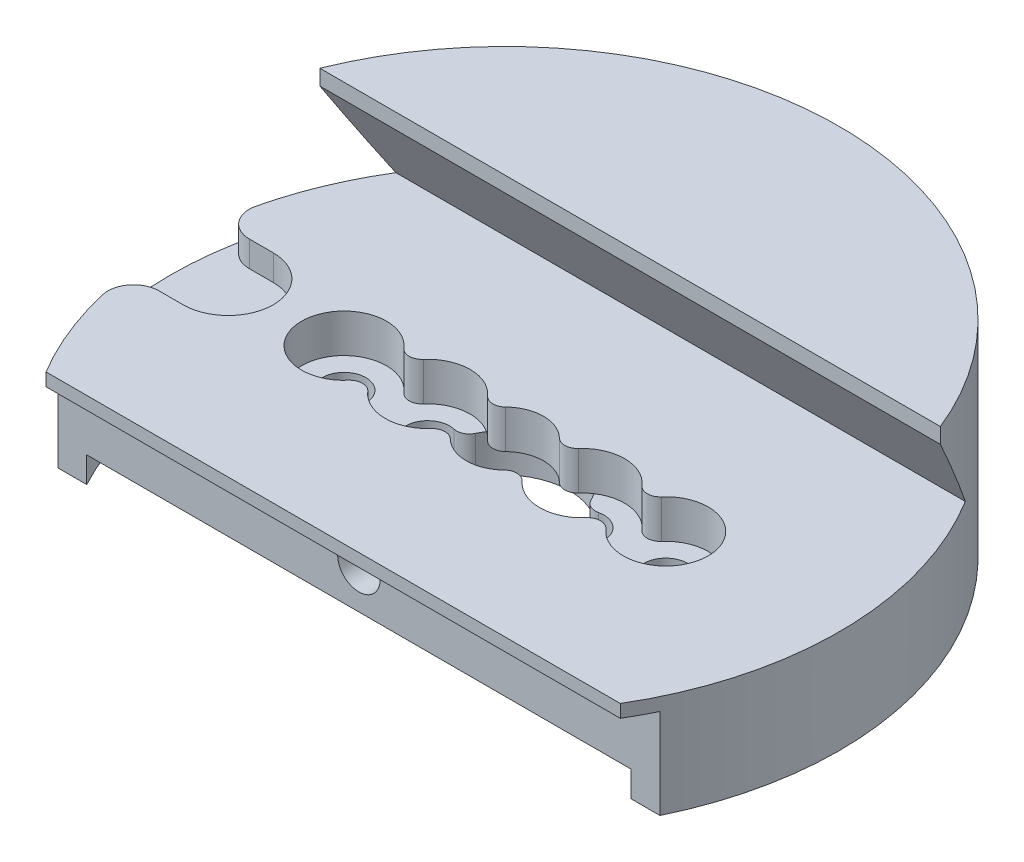
SolidWorks part; units mm, degrees
material "Сплав 2024"
ref_plane "Спереди" through (0, 0, 0) normal (0, 0, 1) x (1, 0, 0)
ref_plane "Сверху" through (0, 0, 0) normal (0, 1, 0) x (1, 0, 0)
ref_plane "Справа" through (0, 0, 0) normal (1, 0, 0) x (0, 0, -1)
sketch "Эскиз1" plane through (0, 0, 0) normal (0, 1, 0) x (1, 0, 0)
  circle A0 centre (0, 0) radius 26
  dimension "D1" = 52
extrude "Бобышка-Вытянуть1" add sketch "Эскиз1" along normal blind 14
sketch "Эскиз2" plane through (0, 0, 0) normal (1, 0, 0) x (0, 0, -1)
  line L0 (0, 14) -> (0, 0) construction
  line L1 (26, 14) -> (-26, 14) construction
  line L2 (13.6547, 6) -> (-13.6547, 6)
  line L3 (-13.6547, 6) -> (-9.7287, 12.8)
  line L4 (-9.7287, 12.8) -> (-9.7287, 14)
  line L5 (-9.7287, 14) -> (9.7287, 14)
  line L6 (0, 14) -> (0, 6) construction
  line L7 (13.6547, 6) -> (9.7287, 12.8)
  line L8 (9.7287, 12.8) -> (9.7287, 14)
  line L9 (-12.5, 8) -> (-12.5, 6) construction
  dimension "D1" = 8
  dimension "D2" = 1.2
  dimension "D3" = 60
  dimension "D4" = 13.6547
  dimension "D5" = 9.7287
  dimension "D6" = 2
  dimension "D7" = 12.5
extrude "Вырез-Вытянуть1" cut sketch "Эскиз2" against normal mid plane 60
sketch "Примерка" plane through (0, 0, 0) normal (1, 0, 0) x (0, 0, -1)
  line L0 (13.6547, 6) -> (-13.6547, 6) construction
  line L1 (-12.5, 14) -> (12.5, 14)
  line L2 (-12.5, 14) -> (-12.5, 6)
  line L3 (-12.5, 6) -> (12.5, 6)
  line L4 (12.5, 14) -> (12.5, 6)
  point P6 (0, 6)
  dimension "D1" = 8
  dimension "D2" = 25
sketch "Эскиз5" plane through (0, 0, 0) normal (0, -1, 0) x (1, 0, 0)
  line L2 (-22.1258, -15.6547) -> (22.1258, -15.6547)
  line L3 (-18.1915, -15.6547) -> (18.1915, -15.6547)
  circle A2 centre (0, 0) radius 24
  arc A3 (-18.1915, -15.6547) -> (18.1915, -15.6547) centre (0, 0) ccw
  dimension "D1" = 2
  dimension "D2" = 2
extrude "Вырез-Вытянуть3" cut sketch "Эскиз5" against normal offset from surface (12 mm away) 2 up to face at (0, 14, -17.8644)
sketch "Эскиз6" plane through (0, 6, 0) normal (0, 1, 0) x (1, 0, 0)
  line L1 (18.4208, 0) -> (-15.4735, 0) construction
  circle A0 centre (0, 0) radius 6 construction
  circle A1 centre (0, 0) radius 12.5 construction
  dimension "D1" = 12
  dimension "D2" = 25
hole_wizard "Цековка для винта с внутренним шестигранником M32" positions "Эскиз14" profile "Эскиз13" counterbore size "M3" standard "Ansi Metric" end condition up to next
sketch "Эскиз14" plane through (0, 6, 0) normal (0, 1, 0) x (1, 0, 0)
  line L0 (18.4208, 0) -> (-15.4735, 0) construction
  circle A0 centre (0, 0) radius 12.5 construction
  circle A1 centre (0, 0) radius 6 construction
  point P0 (-12.5, 0)
  point P6 (12.5, 0)
  point P20 (-6, 0)
  point P24 (6, 0)
sketch "Эскиз13" plane through (-12.5, 6, 0) normal (1, 0, 0) x (0, 0, 1)
  line L0 (0, 0) -> (0, 6)
  line L1 (0, 6) -> (1.7, 6)
  line L3 (1.7, 6) -> (1.7, 3)
  line L4 (1.7, 3) -> (3.3, 3)
  line L5 (3.3, 3) -> (3.3, 0)
  line L7 (3.3, 0) -> (0, 0)
  line L11 (0, -6.35) -> (0, 107.95) construction
  dimension "Диаметр сквозного отверстия" = 3.4
  dimension "Глубина сквозного отверстия" = 6
  dimension "Диаметр цековки" = 6.6
  dimension "Глубина цековки" = 3
sketch "Эскиз12" plane through (0, 0, 0) normal (0, -1, 0) x (1, 0, 0)
  circle A0 centre (0, 0) radius 26 construction
  circle A1 centre (0, 0) radius 26
  circle A3 centre (0, 0) radius 24
  dimension "D1" = 2
extrude "Бобышка-Вытянуть2" add sketch "Эскиз12" along normal blind 2
sketch "Эскиз17" plane through (0, 14, 0) normal (0, 1, 0) x (1, 0, 0)
  line L0 (-24.1112, -9.7287) -> (24.1112, -9.7287) construction
  line L1 (-24.1112, -9.7287) -> (24.1112, -9.7287)
  arc A0 (-24.1112, -9.7287) -> (24.1112, -9.7287) centre (0, 0) ccw construction
  arc A1 (-24.1112, -9.7287) -> (24.1112, -9.7287) centre (0, 0) ccw
extrude "Вырез-Вытянуть4" cut sketch "Эскиз17" against normal up to surface (8 mm away) up to face at (9.25, 6, 0)
sketch "Эскиз18" plane through (0, 0, 0) normal (0, -1, 0) x (1, 0, 0)
  circle A0 centre (0, 0) radius 5
  dimension "D1" = 10
extrude "Вырез-Вытянуть5" cut sketch "Эскиз18" against normal blind 3
sketch "Эскиз19" plane through (0, 6, 0) normal (0, 1, 0) x (1, 0, 0)
  line L0 (-22.3137, -13.3453) -> (22.3137, -13.3453)
  line L1 (-22.1258, 13.6547) -> (22.1258, 13.6547) construction
  arc A0 (-22.1258, 13.6547) -> (22.1258, 13.6547) centre (0, 0) ccw construction
  arc A1 (-22.3137, -13.3453) -> (22.3137, -13.3453) centre (0, 0) ccw
  dimension "D1" = 27
extrude "Вырез-Вытянуть6" cut sketch "Эскиз19" against normal blind 10
sketch "Эскиз21" plane through (0, 0, 13.3453) normal (0, 0, 1) x (1, 0, 0)
  line L0 (0, 0) -> (0, 6) construction
  line L1 (19.9475, 0) -> (-19.9475, 0) construction
  line L2 (22.3137, 6) -> (-22.3137, 6) construction
  point P6 (0, 3)
  dimension "D1" = 3
hole_wizard "Отверстие обработанное метчиком M4x0.71" positions "Эскиз23" profile "Эскиз22" tap size "M4x0.7" standard "Ansi Metric"
sketch "Эскиз23" plane through (0, 0, 13.3453) normal (0, 0, 1) x (1, 0, 0)
  point P4 (0, 3)
sketch "Эскиз22" plane through (0, 3, 13.3453) normal (1, 0, 0) x (0, -1, 0)
  line L0 (0, 0) -> (0, 12.4914)
  line L1 (0, 12.4914) -> (1.65, 11.5)
  line L2 (1.65, 11.5) -> (1.65, 0)
  line L5 (1.65, 0) -> (0, 0)
  line L10 (0, 12.4914) -> (-1.65, 11.5) construction
  line L11 (0, -6.35) -> (0, 107.95) construction
  dimension "Диаметр сверла" = 3.3
  dimension "Глубина сверла" = 11.5
  dimension "Угол заточки сверла" = 118
cosmetic thread "Отверстие резьбы1" parameters "D1"=8, "D2"=4
sketch "Эскиз20" plane through (0, 0, 13.3453) normal (0, 0, 1) x (1, 0, 0)
  line L0 (0, 3.1198) -> (0, -5.6063) construction
  line L1 (22.3137, 6) -> (-22.3137, 6) construction
  line L2 (-25.2658, 5) -> (25.2658, 5)
  line L3 (-25.2658, 5) -> (-25.2658, -2)
  line L4 (-25.2658, -2) -> (25.2658, -2)
  line L5 (25.2658, 5) -> (25.2658, -2)
  line L6 (-25.2658, 5) -> (25.2658, -2) construction
  line L7 (-25.2658, -2) -> (25.2658, 5) construction
  line L8 (-22.3137, -2) -> (-19.9475, -2) construction
  point P3 (0, 1.5)
  dimension "D1" = 1
extrude "Вырез-Вытянуть7" cut sketch "Эскиз20" against normal blind 2
sketch "Эскиз24" plane through (0, 6, 0) normal (0, 1, 0) x (1, 0, 0)
  line L0 (-30.5, 0) -> (-21.5, 0) construction
  line L1 (-30.5, 3.5) -> (-21.5, 3.5)
  line L2 (-30.5, -3.5) -> (-21.5, -3.5)
  line L4 (0, 0) -> (-6.6582, 0) construction
  arc A0 (-22.1258, 13.6547) -> (-22.3137, -13.3453) centre (0, 0) ccw construction
  arc A1 (-30.5, 3.5) -> (-30.5, -3.5) centre (-30.5, 0) ccw
  arc A2 (-21.5, -3.5) -> (-21.5, 3.5) centre (-21.5, 0) ccw
  point P5 (-26, 0)
  dimension "D1" = 9
  dimension "D2" = 7
extrude "Вырез-Вытянуть8" cut sketch "Эскиз24" against normal blind 2
fillet "Скругление3" radius 2 2 edges at (-25.7633, 5, 3.5) (-25.7633, 5, -3.5)
fillet "Скругление4" radius 4 2 edges
sketch "Эскиз25" plane through (0, 3, 0) normal (0, -1, 0) x (1, 0, 0)
  circle A0 centre (0, 0) radius 3
  dimension "D1" = 6
extrude "Вырез-Вытянуть9" cut sketch "Эскиз25" against normal up to next
fillet "Скругление2" radius 1 12 edges at (9.25, 4.5, 0.5723) (9.25, 4.5, -0.5723) (-9.25, 4.5, -0.5723) (-9.25, 4.5, 0.5723) (-2.8425, 4.5, 0.9593) (-2.8425, 4.5, -0.9593) (2.8425, 4.5, 0.9593) (2.8425, 4.5, -0.9593) (4.8425, 1.5, 1.2451) (4.8425, 1.5, -1.2451) (-4.8425, 1.5, -1.2451) (-4.8425, 1.5, 1.2451)
